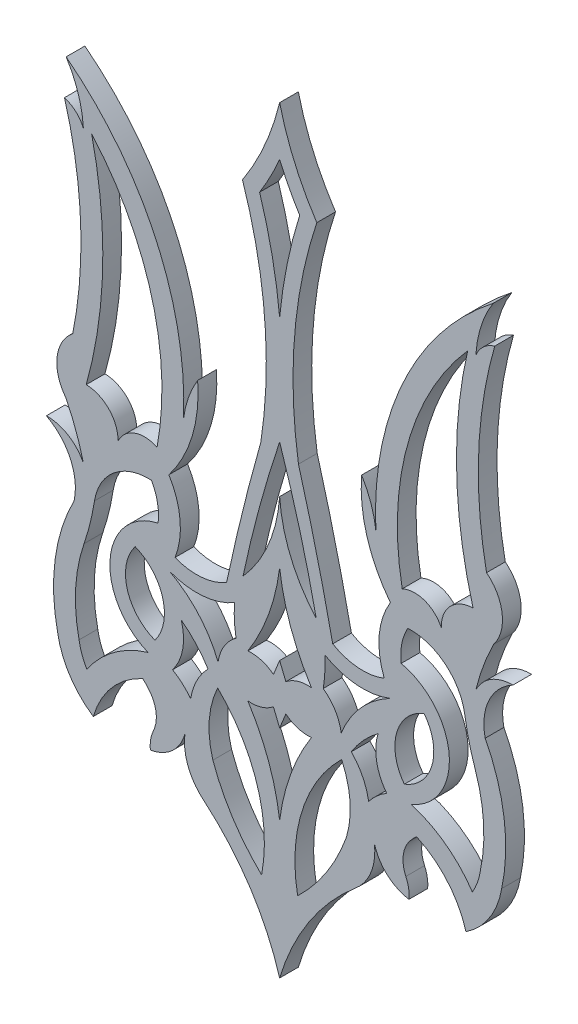
SolidWorks part; units mm, degrees
ref_plane "Спереди" through (0, 0, 0) normal (0, 0, 1) x (1, 0, 0)
ref_plane "Сверху" through (0, 0, 0) normal (0, 1, 0) x (1, 0, 0)
ref_plane "Справа" through (0, 0, 0) normal (1, 0, 0) x (0, 0, -1)
sketch "Эскиз3" plane through (0, 0, 0) normal (0, 0, 1) x (1, 0, 0)
  line L0 (87.6443, -0.7518) -> (87.6443, -30.7439) construction
  line L1 (75.7373, 214.8271) -> (99.5514, 214.8271) construction
  line L2 (87.6443, 214.8271) -> (87.6443, 245.1652) construction
  arc A0 (75.7373, 214.8271) -> (87.6443, 242.1865) centre (3.1746, 262.6778) ccw
  arc A2 (75.7373, 214.8271) -> (81.6055, 144.874) centre (-65.9765, 167.7164) cw
  arc A3 (81.6055, 144.874) -> (70.6377, 100.4834) centre (729.5469, -38.7656) ccw
  arc A4 (70.6377, 100.4834) -> (54.1195, 99.18) centre (61.0278, 116.9518) cw
  arc A5 (54.1195, 99.18) -> (52.147, 121.1645) centre (31.2493, 108.2088) ccw
  arc A6 (52.147, 121.1645) -> (61.3729, 151.9663) centre (17.0866, 148.4485) ccw
  arc A7 (61.3729, 151.9663) -> (56.8067, 138.8308) centre (89.4398, 134.8482) ccw
  arc A8 (56.8067, 138.8308) -> (19.2332, 220.6949) centre (-40.5564, 143.6983) ccw
  arc A9 (19.2332, 220.6949) -> (24.7593, 203.6092) centre (-10.9905, 201.483) cw
  arc A10 (24.7593, 203.6092) -> (18.7084, 209.1008) centre (15.8046, 199.8218) ccw
  arc A11 (18.7084, 209.1008) -> (21.3399, 144.8893) centre (-112.1058, 171.5801) cw
  arc A12 (21.3399, 144.8893) -> (19.102, 126.0824) centre (29.6244, 134.3669) ccw
  arc A13 (19.102, 126.0824) -> (24.7805, 110.6673) centre (-47.0296, 92.9675) cw
  arc A14 (24.7805, 110.6673) -> (12.8982, 117.9136) centre (13.0914, 104.8649) ccw
  arc A15 (12.8982, 117.9136) -> (21.781, 98.7337) centre (4.7748, 102.5045) cw
  arc A16 (21.781, 98.7337) -> (16.4854, 59.6475) centre (73.3534, 71.8446) ccw
  arc A17 (16.4854, 59.6475) -> (27.9301, 41.9549) centre (42.5937, 63.9882) ccw
  arc A18 (27.9301, 41.9549) -> (43.7562, 60.4021) centre (55.9548, 33.9245) cw
  arc A19 (43.7562, 60.4021) -> (46.0707, 57.9309) centre (32.5904, 47.6247) cw
  arc A20 (47.2033, 47.6608) -> (46.2055, 41.7904) centre (57.5332, 42.885) ccw
  arc A21 (46.2055, 41.7904) -> (57.3048, 51.8905) centre (44.028, 55.3321) ccw
  arc A22 (57.3048, 51.8905) -> (63.4952, 36.2204) centre (74.3192, 49.5541) ccw
  arc A23 (63.4952, 36.2204) -> (87.6443, -0.7518) centre (13.2717, -22.957) cw
  arc A24 (111.7935, 36.2204) -> (87.6443, -0.7518) centre (162.017, -22.957) ccw
  arc A25 (117.9838, 51.8905) -> (111.7935, 36.2204) centre (100.9695, 49.5541) cw
  arc A26 (129.0831, 41.7904) -> (117.9838, 51.8905) centre (131.2607, 55.3321) cw
  arc A27 (128.0854, 47.6608) -> (129.0831, 41.7904) centre (117.7555, 42.885) cw
  arc A28 (131.5325, 60.4021) -> (129.218, 57.9309) centre (142.6983, 47.6247) ccw
  arc A29 (147.3585, 41.9549) -> (131.5325, 60.4021) centre (119.3338, 33.9245) ccw
  arc A30 (158.8033, 59.6475) -> (147.3585, 41.9549) centre (132.695, 63.9882) cw
  arc A31 (153.5077, 98.7337) -> (158.8033, 59.6475) centre (101.9353, 71.8446) cw
  arc A32 (162.3905, 117.9136) -> (153.5077, 98.7337) centre (170.5139, 102.5045) ccw
  arc A33 (150.5081, 110.6673) -> (162.3905, 117.9136) centre (162.1973, 104.8649) cw
  arc A34 (156.1867, 126.0824) -> (150.5081, 110.6673) centre (222.3183, 92.9675) ccw
  arc A35 (153.9488, 144.8893) -> (156.1867, 126.0824) centre (145.6643, 134.3669) cw
  arc A36 (156.5803, 209.1008) -> (153.9488, 144.8893) centre (287.3945, 171.5801) ccw
  arc A37 (150.5293, 203.6092) -> (156.5803, 209.1008) centre (159.4841, 199.8218) cw
  arc A38 (156.0554, 220.6949) -> (150.5293, 203.6092) centre (186.2792, 201.483) ccw
  arc A39 (118.482, 138.8308) -> (156.0554, 220.6949) centre (215.8451, 143.6983) cw
  arc A40 (113.9158, 151.9663) -> (118.482, 138.8308) centre (85.8489, 134.8482) cw
  arc A41 (123.1417, 121.1645) -> (113.9158, 151.9663) centre (158.202, 148.4485) cw
  arc A42 (121.1692, 99.18) -> (123.1417, 121.1645) centre (144.0394, 108.2088) cw
  arc A43 (104.651, 100.4834) -> (121.1692, 99.18) centre (114.2609, 116.9518) ccw
  arc A44 (93.6832, 144.874) -> (104.651, 100.4834) centre (-554.2582, -38.7656) cw
  arc A45 (99.5514, 214.8271) -> (93.6832, 144.874) centre (241.2652, 167.7164) ccw
  arc A47 (99.5514, 214.8271) -> (87.6443, 242.1865) centre (172.1141, 262.6778) cw
  arc A48 (46.0707, 57.9309) -> (47.2033, 47.6608) centre (38.1265, 51.8573) cw
  arc A49 (129.218, 57.9309) -> (128.0854, 47.6608) centre (137.1622, 51.8573) ccw
  point P110 (49.2752, 50.7157)
  point P113 (126.0135, 50.7157)
  dimension "D1" = 10
  dimension "D2" = 10
extrude "Бобышка-Вытянуть1" add sketch "Эскиз3" along normal blind 6
sketch "Эскиз4" plane through (0, 0, 0) normal (0, 0, 1) x (1, 0, 0)
  line L0 (87.6443, -0.7518) -> (87.6443, -32.3218) construction
  line L1 (85.6546, 73.5186) -> (87.6443, 68.6318)
  line L2 (87.6443, 68.6318) -> (89.6341, 73.5186)
  line L3 (73.672, 78) -> (99.3785, 78) construction
  line L4 (87.6443, 87.3682) -> (89.6341, 82.4814)
  line L5 (85.6546, 82.4814) -> (87.6443, 87.3682)
  arc A0 (87.6443, 148.0034) -> (75.9102, 104.8888) centre (451.7712, 25.7481) ccw
  arc A1 (87.6443, 132.8603) -> (75.9102, 104.8888) centre (41.1732, 135.9081) cw
  arc A2 (67.7808, 69.8254) -> (81.8714, 24.9568) centre (33.1175, 34.2929) cw
  arc A3 (81.8714, 24.9568) -> (66.2431, 49.0031) centre (124.8767, 70.0089) cw
  arc A4 (66.2431, 49.0031) -> (67.7808, 69.8254) centre (94.1751, 57.4083) cw
  arc A5 (87.6443, 42.9742) -> (77.4425, 71.0893) centre (20.2867, 34.4413) ccw
  arc A7 (64.6822, 73.5186) -> (56.1084, 82.846) centre (35.8416, 55.6125) ccw
  arc A8 (64.6822, 73.5186) -> (59.1188, 62.4923) centre (79.1678, 59.2931) ccw
  arc A9 (53.3348, 67.6488) -> (56.1084, 82.846) centre (40.0944, 77.917) ccw
  arc A10 (59.1188, 62.4923) -> (53.3348, 67.6488) centre (43.2754, 50.5432) ccw
  arc A12 (67.908, 77.0685) -> (52.3079, 94.5198) centre (36.5563, 64.7406) ccw
  arc A13 (67.908, 77.0685) -> (73.672, 86.5781) centre (82.0844, 74.9775) cw
  arc A14 (73.672, 86.5781) -> (73.1577, 96.1649) centre (115.3568, 93.6216) cw
  arc A15 (41.3552, 95.8164) -> (47.6907, 73.0153) centre (35.854, 82.0071) cw
  arc A16 (41.3552, 95.8164) -> (47.6907, 73.0153) centre (52.9673, 86.7622) ccw
  arc A27 (133.9335, 95.8164) -> (127.598, 73.0153) centre (122.3214, 86.7622) cw
  arc A28 (133.9335, 95.8164) -> (127.598, 73.0153) centre (139.4347, 82.0071) ccw
  arc A29 (101.6166, 86.5781) -> (102.131, 96.1649) centre (59.9318, 93.6216) ccw
  arc A30 (107.3806, 77.0685) -> (101.6166, 86.5781) centre (93.2043, 74.9775) ccw
  arc A31 (107.3806, 77.0685) -> (122.9808, 94.5198) centre (138.7324, 64.7406) cw
  arc A33 (116.1699, 62.4923) -> (121.9539, 67.6488) centre (132.0132, 50.5432) cw
  arc A34 (121.9539, 67.6488) -> (119.1803, 82.846) centre (135.1943, 77.917) cw
  arc A35 (110.6065, 73.5186) -> (116.1699, 62.4923) centre (96.1209, 59.2931) cw
  arc A36 (110.6065, 73.5186) -> (119.1803, 82.846) centre (139.4471, 55.6125) cw
  arc A38 (87.6443, 42.9742) -> (97.8462, 71.0893) centre (155.002, 34.4413) cw
  arc A39 (109.0456, 49.0031) -> (107.5079, 69.8254) centre (81.1136, 57.4083) ccw
  arc A40 (93.4173, 24.9568) -> (109.0456, 49.0031) centre (50.412, 70.0089) ccw
  arc A41 (107.5079, 69.8254) -> (93.4173, 24.9568) centre (142.1712, 34.2929) ccw
  arc A42 (87.6443, 132.8603) -> (99.3785, 104.8888) centre (134.1154, 135.9081) ccw
  arc A43 (87.6443, 148.0034) -> (99.3785, 104.8888) centre (-276.4825, 25.7481) cw
  arc A44 (77.4425, 71.0893) -> (85.6546, 73.5186) centre (78.6188, 82.2081) ccw
  arc A45 (97.8462, 71.0893) -> (89.6341, 73.5186) centre (96.6699, 82.2081) cw
  arc A46 (46.5701, 116.8463) -> (28.3164, 101.9946) centre (45.7021, 99.2698) ccw
  arc A47 (24.9573, 88.4367) -> (28.3164, 101.9946) centre (-50.7188, 114.3815) ccw
  arc A49 (48.7004, 106.02) -> (45.4623, 68.5209) centre (52.9673, 86.7622) ccw
  arc A50 (37.4121, 98.8909) -> (45.899, 68.3473) centre (52.9673, 86.7622) ccw construction
  arc A51 (87.6443, 113.0258) -> (77.4425, 84.9107) centre (20.2867, 121.5587) cw
  arc A52 (151.923, 60.9491) -> (149.4021, 53.997) centre (132.695, 63.9882) cw
  arc A53 (47.6085, 101.7505) -> (46.1975, 117.4761) centre (31.2493, 108.2088) ccw
  arc A54 (48.7004, 106.02) -> (46.5701, 116.8463) centre (31.2493, 108.2088) ccw
  arc A55 (129.8264, 68.5209) -> (149.4021, 53.997) centre (119.3338, 33.9245) cw
  arc A56 (150.3314, 88.4367) -> (146.9723, 101.9946) centre (226.0075, 114.3815) cw
  arc A57 (150.3314, 88.4367) -> (151.923, 60.9491) centre (101.9353, 71.8446) cw
  arc A58 (126.5883, 106.02) -> (129.8264, 68.5209) centre (122.3214, 86.7622) cw
  arc A59 (128.7186, 116.8463) -> (146.9723, 101.9946) centre (129.5865, 99.2698) cw
  arc A60 (126.5883, 106.02) -> (128.7186, 116.8463) centre (144.0394, 108.2088) cw
  arc A61 (87.6443, 113.0258) -> (97.8462, 84.9107) centre (155.002, 121.5587) ccw
  arc A62 (97.8462, 84.9107) -> (89.6341, 82.4814) centre (96.6699, 73.7919) ccw
  arc A63 (77.4425, 84.9107) -> (85.6546, 82.4814) centre (78.6188, 73.7919) cw
  arc A75 (28.3709, 96.2178) -> (16.1626, 124.1058) centre (4.7748, 102.5045) ccw
  arc A76 (23.3657, 60.9491) -> (25.8866, 53.997) centre (42.5937, 63.9882) ccw
  arc A77 (28.3709, 96.2178) -> (23.3657, 60.9491) centre (73.3534, 71.8446) ccw
  arc A78 (40.8271, 66.7598) -> (25.8866, 53.997) centre (55.9548, 33.9245) ccw
  arc A80 (23.3657, 60.9491) -> (25.8866, 53.997) centre (42.5937, 63.9882) ccw
  arc A81 (24.9573, 88.4367) -> (23.3657, 60.9491) centre (73.3534, 71.8446) ccw
  arc A82 (45.4623, 68.5209) -> (25.8866, 53.997) centre (55.9548, 33.9245) ccw
  arc A266 (49.8154, 139.1803) -> (14.94, 215.166) centre (-40.5564, 143.6983) ccw
  arc A267 (48.3554, 126.9004) -> (27.3869, 203.4577) centre (-40.5564, 143.6983) ccw
  arc A268 (25.6623, 132.9232) -> (35.854, 122.3882) centre (25.4906, 122.5599) cw
  arc A269 (28.204, 143.5164) -> (25.4371, 211.0307) centre (-112.1058, 171.5801) ccw
  arc A270 (25.6623, 132.9232) -> (27.3869, 203.4577) centre (-112.1058, 171.5801) ccw
  arc A271 (35.854, 122.3882) -> (48.3554, 126.9004) centre (44.3608, 118.3936) cw
  arc A279 (139.4347, 122.3882) -> (126.9333, 126.9004) centre (130.9279, 118.3936) ccw
  arc A280 (149.6264, 132.9232) -> (139.4347, 122.3882) centre (149.798, 122.5599) ccw
  arc A281 (149.6264, 132.9232) -> (147.9018, 203.4577) centre (287.3945, 171.5801) cw
  arc A282 (126.9333, 126.9004) -> (147.9018, 203.4577) centre (215.8451, 143.6983) cw
  arc A322 (94.0669, 214.1199) -> (88.742, 144.1093) centre (241.2652, 167.7164) ccw
  arc A323 (82.7853, 241.0077) -> (94.0669, 214.1199) centre (172.1141, 262.6778) ccw
  arc A324 (94.0669, 214.1199) -> (87.6443, 182.5908) centre (241.2652, 167.7164) ccw
  arc A325 (87.6443, 226.4274) -> (94.0669, 214.1199) centre (172.1141, 262.6778) ccw
  arc A328 (122.9808, 94.5198) -> (102.131, 96.1649) centre (114.2609, 116.9518) cw
  arc A329 (86.5466, 144.1093) -> (81.2218, 214.1199) centre (-65.9765, 167.7164) ccw
  arc A330 (81.2218, 214.1199) -> (92.5034, 241.0077) centre (3.1746, 262.6778) ccw
  arc A331 (87.6443, 182.5908) -> (81.2218, 214.1199) centre (-65.9765, 167.7164) ccw
  arc A332 (81.2218, 214.1199) -> (87.6443, 226.4274) centre (3.1746, 262.6778) ccw
  arc A333 (52.3079, 94.5198) -> (73.1577, 96.1649) centre (61.0278, 116.9518) ccw
  arc A334 (52.3079, 94.5198) -> (73.1577, 96.1649) centre (61.0278, 116.9518) ccw
  point P134 (28.7997, 106.8883)
  point P153 (48.7731, 116.5977)
  dimension "D7" = 5
  dimension "D8" = 80
  dimension "D9" = 7
  dimension "D10" = 78
  dimension "D1" = 7
  dimension "D2" = 7
  dimension "D3" = 7
  dimension "D4" = 5
  dimension "D5" = 5
  dimension "D6" = 5
extrude "Вырез-Вытянуть4" cut sketch "Эскиз4" along normal blind 10
scale "Масштаб1" scale about centroid uniform scaling yes scale factor 0.5
